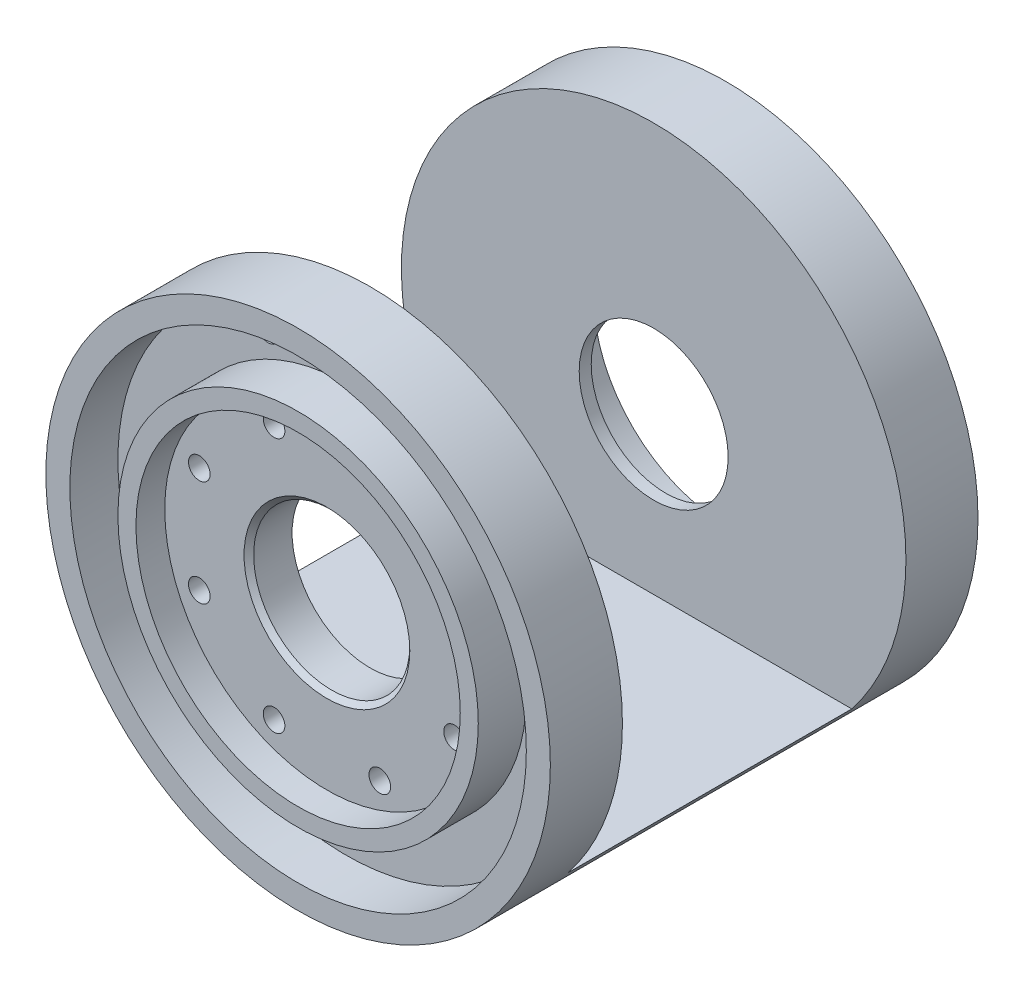
SolidWorks part; units mm, degrees
ref_plane "前视基准面" through (0, 0, 0) normal (0, 0, 1) x (1, 0, 0)
ref_plane "上视基准面" through (0, 0, 0) normal (0, 1, 0) x (1, 0, 0)
ref_plane "右视基准面" through (0, 0, 0) normal (1, 0, 0) x (0, 0, -1)
other "Configuration Table"
sketch "草图1" plane through (0, 0, 0) normal (0, 0, 1) x (1, 0, 0)
  circle A0 centre (0, 0) radius 105
  dimension "D1" = 210
extrude "凸台-拉伸1" add sketch "草图1" along normal mid plane 178
sketch "草图3" plane through (0, 0, 0) normal (0, 0, 1) x (1, 0, 0)
  line L0 (-82.4621, -65) -> (82.4621, -65)
  circle A1 centre (0, 0) radius 105
  arc A2 (82.4621, -65) -> (-82.4621, -65) centre (0, 0) ccw
  dimension "D2" = 170
  dimension "D1" = 0
extrude "切除-拉伸1" cut sketch "草图3" against normal mid plane 118
sketch "草图4" plane through (0, 0, -89) normal (0, 0, -1) x (-1, 0, 0)
  circle A0 centre (0, 0) radius 75
  circle A1 centre (0, 0) radius 95
  dimension "D1" = 150
  dimension "D2" = 190
extrude "切除-拉伸2" cut sketch "草图4" against normal blind 20
sketch "草图5" plane through (0, 0, -89) normal (0, 0, -1) x (-1, 0, 0)
  circle A0 centre (0, 0) radius 55
  dimension "D1" = 110
extrude "切除-拉伸3" cut sketch "草图5" against normal blind 22
sketch "草图6" plane through (0, 0, -67) normal (0, 0, -1) x (-1, 0, 0)
  circle A0 centre (0, 0) radius 50
  dimension "D1" = 100
extrude "切除-拉伸4" cut sketch "草图6" against normal blind 3
sketch "草图7" plane through (0, 0, -64) normal (0, 0, -1) x (-1, 0, 0)
  circle A0 centre (0, 0) radius 31
  dimension "D1" = 62
extrude "切除-拉伸5" cut sketch "草图7" against normal up to next
sketch "草图8" plane through (0, 0, 89) normal (0, 0, 1) x (1, 0, 0)
  circle A0 centre (0, 0) radius 95
  circle A1 centre (0, 0) radius 75
  dimension "D1" = 190
  dimension "D2" = 150
extrude "切除-拉伸6" cut sketch "草图8" against normal blind 20
sketch "草图9" plane through (0, 0, 89) normal (0, 0, 1) x (1, 0, 0)
  circle A0 centre (0, 0) radius 67.5
  dimension "D1" = 135
extrude "切除-拉伸7" cut sketch "草图9" against normal blind 12
sketch "草图10" plane through (0, 0, 77) normal (0, 0, 1) x (1, 0, 0)
  circle A0 centre (0, 0) radius 32.5
  point P2 (0, 0)
  dimension "D1" = 65
extrude "切除-拉伸8" cut sketch "草图10" against normal up to next
chamfer "倒角1" distance 2 angle 45 1 edges at (32.5, 0, 77)
sketch "草图11" plane through (0, 0, 69) normal (0, 0, 1) x (1, 0, 0)
  line L0 (0, 0) -> (0, 84.0689) construction
  circle A0 centre (0, 0) radius 85 construction
  circle A1 centre (0, 85) radius 5
  circle A2 centre (32.5281, 78.5298) radius 5
  circle A3 centre (-32.5281, 78.5298) radius 5
  point P7 (0, 0)
  dimension "D1" = 170
  dimension "D2" = 10
  dimension "D3" = 45
extrude "切除-拉伸9" cut sketch "草图11" against normal up to next
sketch "草图12" plane through (0, 0, 77) normal (0, 0, 1) x (1, 0, 0)
  line L0 (-32.5281, 78.5298) -> (0, 0) construction
  circle A0 centre (0, 0) radius 57.5 construction
  circle A2 centre (22.0043, 53.1231) radius 4.5
  circle A3 centre (53.1231, 22.0043) radius 4.5
  circle A4 centre (53.1231, -22.0043) radius 4.5
  circle A5 centre (22.0043, -53.1231) radius 4.5
  circle A6 centre (-22.0043, -53.1231) radius 4.5
  circle A7 centre (-53.1231, -22.0043) radius 4.5
  circle A8 centre (-53.1231, 22.0043) radius 4.5
  circle A9 centre (-22.0043, 53.1231) radius 4.5
  point P5 (0, 0)
  point P22 (0, 0)
  dimension "D1" = 115
  dimension "D2" = 9
  dimension "D3" = 8
extrude "切除-拉伸10" cut sketch "草图12" against normal up to next
